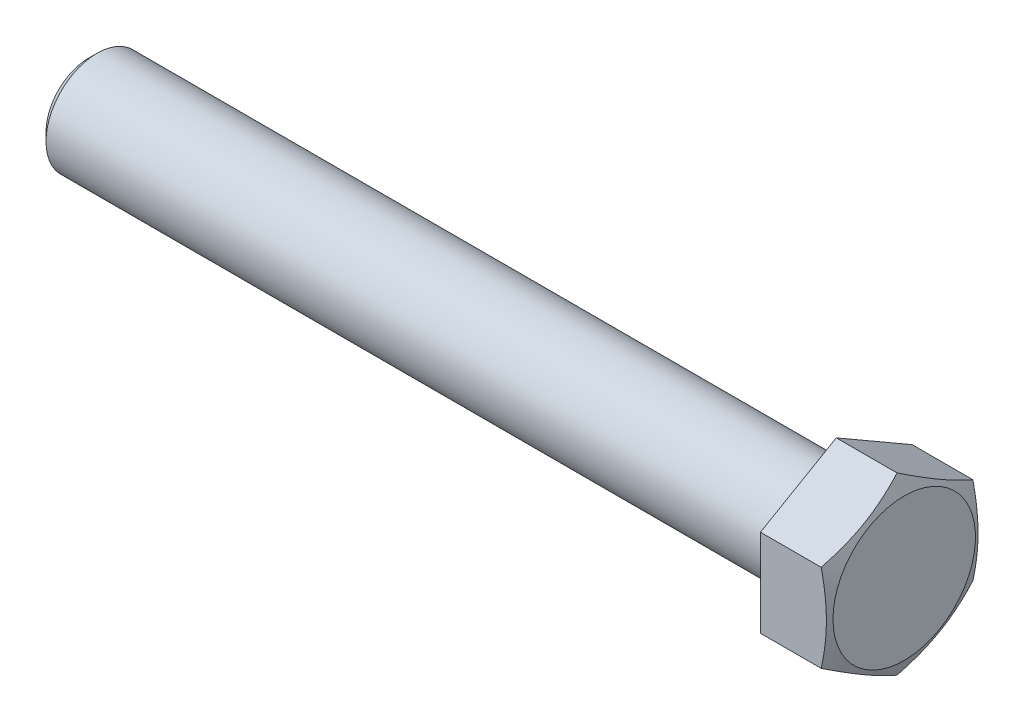
SolidWorks part; units mm, degrees
material "AISI 1035 STEEL"
ref_plane "Front Plane" through (0, 0, 0) normal (0, 0, 1) x (1, 0, 0)
ref_plane "Top Plane" through (0, 0, 0) normal (0, 1, 0) x (1, 0, 0)
ref_plane "Right Plane" through (0, 0, 0) normal (1, 0, 0) x (0, 0, -1)
sketch "Sketch1" plane through (0, 0, 0) normal (1, 0, 0) x (0, 0, -1)
  line L1 (0, 8.1829) -> (-7.0866, 4.0915)
  line L2 (-7.0866, 4.0915) -> (-7.0866, -4.0915)
  line L3 (-7.0866, -4.0915) -> (0, -8.1829)
  line L4 (0, -8.1829) -> (7.0866, -4.0915)
  line L5 (7.0866, -4.0915) -> (7.0866, 4.0915)
  line L6 (7.0866, 4.0915) -> (0, 8.1829)
  circle A0 centre (0, 0) radius 7.0866 construction
  dimension "D1" = 14.1732
extrude "HEX-HEAD" add sketch "Sketch1" along normal blind 6.35
sketch "Sketch2" plane through (0, 0, 0) normal (0, 0, 1) x (1, 0, 0)
  line L0 (6.35, 6.6589) -> (5.6773, 8.1829)
  line L1 (6.35, 8.1829) -> (6.35, 4.0915) construction
  line L2 (6.35, 8.1829) -> (0, 8.1829) construction
  line L3 (5.6773, 8.1829) -> (6.35, 8.1829)
  line L4 (6.35, 8.1829) -> (6.35, 6.6589)
  line L6 (0, 0) -> (9.619, 0) construction
  dimension "D1" = 0.6727
  dimension "D2" = 1.524
revolve "EDGE-CUT" cut sketch "Sketch2" angle 360 about L6
sketch "Sketch3" plane through (0, 0, 0) normal (-1, 0, 0) x (0, 0, 1)
  circle A0 centre (0, 0) radius 4.7625
  dimension "D1" = 9.525
extrude "BOLT-BODY" add sketch "Sketch3" along normal blind 69.85
cosmetic thread "Cosmetic Thread1" parameters "D1"=25.4, "D2"=8.525
chamfer "Chamfer1" distance 0.762 angle 45 1 edges at (-69.85, 0, 4.7625)
fillet "Fillet1" radius 0.381 1 edges at (0, 0, -4.7625)
